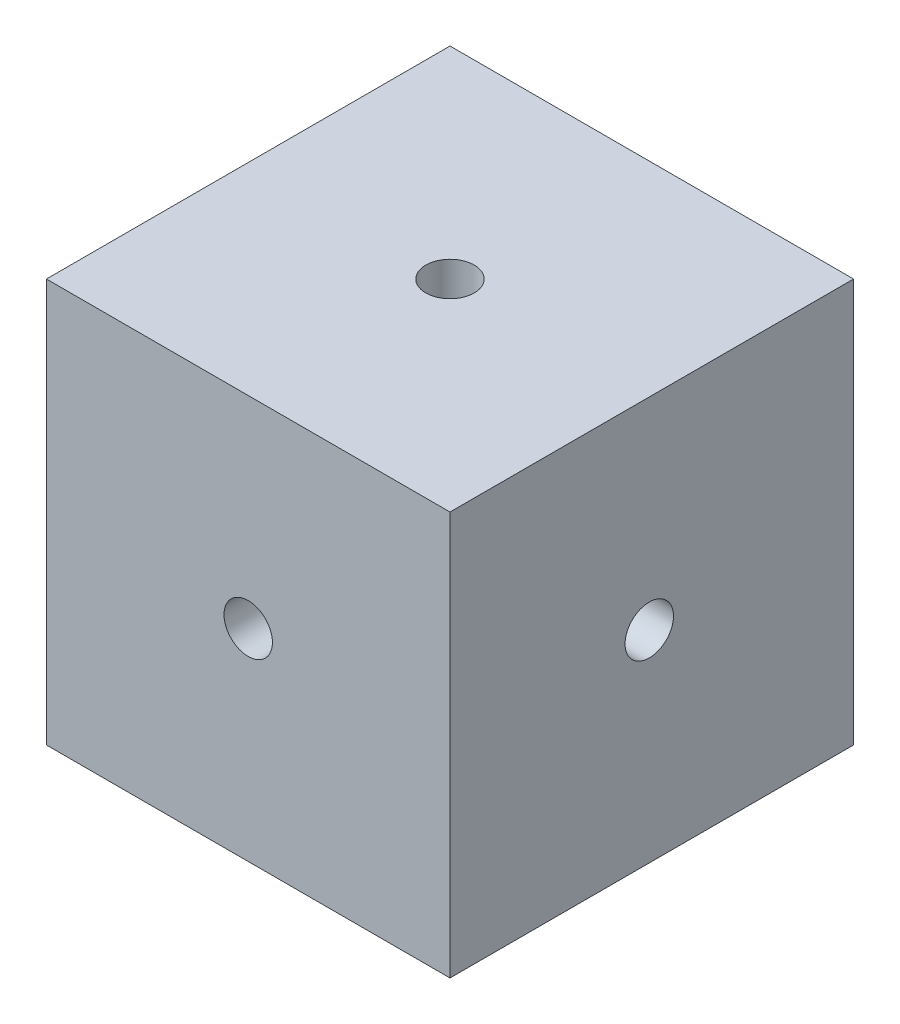
SolidWorks part; units mm, degrees
ref_plane "Front Plane" through (0, 0, 0) normal (0, 0, 1) x (1, 0, 0)
ref_plane "Top Plane" through (0, 0, 0) normal (0, 1, 0) x (1, 0, 0)
ref_plane "Right Plane" through (0, 0, 0) normal (1, 0, 0) x (0, 0, -1)
sketch "Sketch1" plane through (0, 0, 0) normal (0, 0, 1) x (1, 0, 0)
  line L1 (-12.5, -12.5) -> (12.5, -12.5)
  line L2 (-12.5, -12.5) -> (-12.5, 12.5)
  line L3 (-12.5, 12.5) -> (12.5, 12.5)
  line L4 (12.5, -12.5) -> (12.5, 12.5)
  line L5 (-12.5, -12.5) -> (12.5, 12.5) construction
  line L6 (-12.5, 12.5) -> (12.5, -12.5) construction
  point P0 (0, 0)
  dimension "D1" = 25
  dimension "D2" = 25
extrude "Boss-Extrude3" add sketch "Sketch1" along normal blind 25
sketch "Sketch3" plane through (0, 12.5, 0) normal (0, 1, 0) x (1, 0, 0)
  line L0 (12.5, 0) -> (-12.5, 0) construction
  line L3 (-12.5, -25) -> (-12.5, 0) construction
  circle A0 centre (0, -12.5) radius 1.5
  dimension "D1" = 12.5
  dimension "D2" = 12.5
  dimension "D3" = 3
extrude "Cut-Extrude1" cut sketch "Sketch3" against normal blind 7
sketch "Sketch4" plane through (0, 0, 25) normal (0, 0, 1) x (1, 0, 0)
  circle A0 centre (0, 0) radius 1.5
  dimension "D1" = 3
sketch "Sketch5" plane through (12.5, 0, 0) normal (1, 0, 0) x (0, 0, -1)
  line L0 (0, -12.5) -> (0, 12.5) construction
  line L1 (-25, 12.5) -> (0, 12.5) construction
  circle A0 centre (-12.6562, 0) radius 1.5
  dimension "D1" = 3
  dimension "D2" = 12.6562
  dimension "D3" = 12.5
extrude "Cut-Extrude2" cut sketch "Sketch4" against normal blind 7
extrude "Cut-Extrude3" cut sketch "Sketch5" against normal blind 7
sketch "Sketch6" plane through (0, 0, 0) normal (0, 0, -1) x (-1, 0, 0)
  circle A0 centre (0, 0) radius 1.5
  dimension "D1" = 3
extrude "Cut-Extrude4" cut sketch "Sketch6" against normal blind 7
sketch "Sketch7" plane through (-12.5, 0, 0) normal (-1, 0, 0) x (0, 0, 1)
  line L0 (0, 12.5) -> (0, -12.5) construction
  line L1 (25, -12.5) -> (0, -12.5) construction
  circle A0 centre (12.5, 0) radius 1.5
  dimension "D1" = 3
  dimension "D2" = 12.5
  dimension "D3" = 12.5
extrude "Cut-Extrude5" cut sketch "Sketch7" against normal blind 7
